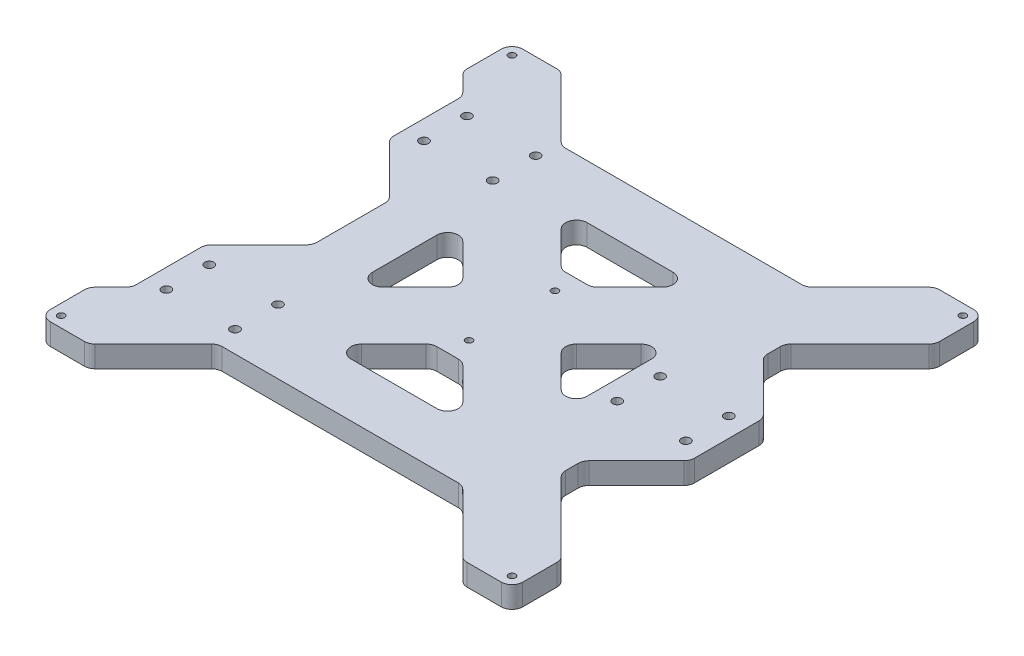
SolidWorks part; units mm, degrees
material "Стекло"
ref_plane "Спереди" through (0, 0, 0) normal (0, 0, 1) x (1, 0, 0)
ref_plane "Сверху" through (0, 0, 0) normal (0, 1, 0) x (1, 0, 0)
ref_plane "Справа" through (0, 0, 0) normal (1, 0, 0) x (0, 0, -1)
sketch "Эскиз1" plane through (0, 0, 0) normal (0, 1, 0) x (1, 0, 0)
  line L0 (-91.6084, 0) -> (86.7133, 0) construction
  line L1 (0, 12.0467) -> (0, -12.5306) construction
  line L2 (-275.537, 125) -> (163.8032, 125) construction
  line L3 (-105, 105) -> (105, 105) construction
  line L4 (-105, 105) -> (-105, -105) construction
  line L5 (-105, -105) -> (105, -105) construction
  line L6 (105, 105) -> (105, -105) construction
  line L7 (-105, 105) -> (105, -105) construction
  line L8 (-105, -105) -> (105, 105) construction
  line L9 (-105, 110) -> (-89.1421, 110)
  line L10 (-55, 125) -> (55, 125) construction
  line L11 (-55, 125) -> (-55, 80) construction
  line L12 (-55, 80) -> (55, 80)
  line L13 (55, 125) -> (55, 80) construction
  line L14 (58.5355, 81.4645) -> (85.6066, 108.5355)
  line L15 (105, 110) -> (89.1421, 110)
  line L16 (-110, 105) -> (-110, 89.1421)
  line L17 (-75, 244.1659) -> (-75, -244.1659) construction
  line L18 (75, 229.144) -> (75, -229.144) construction
  line L19 (-85.6066, 108.5355) -> (-58.5355, 81.4645)
  line L20 (-55, 75) -> (-95, 75) construction
  line L21 (-55, 75) -> (-55, 45) construction
  line L22 (-55, 45) -> (-95, 45) construction
  line L23 (-95, 75) -> (-95, 45) construction
  line L24 (-55, 75) -> (-95, 45) construction
  line L25 (-55, 45) -> (-95, 75) construction
  line L26 (-55, -45) -> (-95, -45) construction
  line L27 (-55, -45) -> (-55, -75) construction
  line L28 (-55, -75) -> (-95, -75) construction
  line L29 (-95, -45) -> (-95, -75) construction
  line L30 (-55, -45) -> (-95, -75) construction
  line L31 (-55, -75) -> (-95, -45) construction
  line L32 (-101.4645, 78.5355) -> (-108.5355, 85.6066)
  line L33 (-100, 45) -> (-100, 75)
  line L34 (-98.5355, 41.4645) -> (-76.4645, 19.3934)
  line L35 (-110, -105) -> (-110, -89.1421)
  line L36 (-76.4645, -19.3934) -> (-98.5355, -41.4645)
  line L37 (-100, -45) -> (-100, -75)
  line L38 (-101.4645, -78.5355) -> (-108.5355, -85.6066)
  line L39 (-75, 15.8579) -> (-75, -15.8579)
  line L40 (110, 105) -> (110, 89.1421)
  line L41 (95, -15) -> (55, -15) construction
  line L42 (95, -15) -> (95, 15) construction
  line L43 (95, 15) -> (55, 15) construction
  line L44 (55, -15) -> (55, 15) construction
  line L45 (95, -15) -> (55, 15) construction
  line L46 (95, 15) -> (55, -15) construction
  line L47 (108.5355, 85.6066) -> (76.4645, 53.5355)
  line L48 (75, 50) -> (75, 44.1421)
  line L49 (98.5355, 18.5355) -> (76.4645, 40.6066)
  line L50 (100, 15) -> (100, -15)
  line L51 (110, -105) -> (110, -89.1421)
  line L52 (108.5355, -85.6066) -> (76.4645, -53.5355)
  line L53 (98.5355, -18.5355) -> (76.4645, -40.6066)
  line L54 (75, -44.1421) -> (75, -50)
  line L55 (-105, -110) -> (-89.1421, -110)
  line L56 (105, -110) -> (89.1421, -110)
  line L57 (-58.5355, -81.4645) -> (-85.6066, -108.5355)
  line L58 (58.5355, -81.4645) -> (85.6066, -108.5355)
  line L59 (-159.2512, -80) -> (161.4197, -80) construction
  line L60 (-55, -80) -> (55, -80)
  line L61 (-23.5355, -46.4645) -> (-8.5355, -31.4645)
  line L62 (-91, 70) -> (-59, 70) construction
  line L63 (-91, 70) -> (-91, 50) construction
  line L64 (-91, 50) -> (-59, 50) construction
  line L65 (-59, 70) -> (-59, 50) construction
  line L66 (-91, 70) -> (-59, 50) construction
  line L67 (-91, 50) -> (-59, 70) construction
  line L68 (-91, -70) -> (-59, -70) construction
  line L69 (-91, -70) -> (-91, -50) construction
  line L70 (-91, -50) -> (-59, -50) construction
  line L71 (-59, -70) -> (-59, -50) construction
  line L72 (-91, -70) -> (-59, -50) construction
  line L73 (-91, -50) -> (-59, -70) construction
  line L74 (59, 10) -> (91, 10) construction
  line L75 (59, 10) -> (59, -10) construction
  line L76 (59, -10) -> (91, -10) construction
  line L77 (91, 10) -> (91, -10) construction
  line L78 (59, 10) -> (91, -10) construction
  line L79 (59, -10) -> (91, 10) construction
  line L80 (-13.5, 25) -> (13.5, 25) construction
  line L81 (-13.5, 25) -> (-13.5, -25) construction
  line L82 (-13.5, -25) -> (13.5, -25) construction
  line L83 (13.5, 25) -> (13.5, -25) construction
  line L84 (-13.5, 25) -> (13.5, -25) construction
  line L85 (-13.5, -25) -> (13.5, 25) construction
  line L86 (23.5355, 46.4645) -> (8.5355, 31.4645)
  line L87 (23.5355, -46.4645) -> (8.5355, -31.4645)
  line L88 (-5, 30) -> (5, 30)
  line L89 (-20, 55) -> (20, 55)
  line L90 (-23.5355, 46.4645) -> (-8.5355, 31.4645)
  line L91 (-20, -55) -> (20, -55)
  line L92 (-5, -30) -> (5, -30)
  line L93 (-50, 15) -> (-50, -15)
  line L94 (-41.4645, 18.5355) -> (-26.4645, 3.5355)
  line L95 (-41.4645, -18.5355) -> (-26.4645, -3.5355)
  line L96 (-18.5, -10) -> (-18.5, 15)
  line L97 (41.4645, 18.5355) -> (26.4645, 3.5355)
  line L98 (41.4645, -18.5355) -> (26.4645, -3.5355)
  line L99 (50, 15) -> (50, -15)
  arc A0 (-105, 110) -> (-110, 105) centre (-105, 105) ccw
  arc A1 (110, 105) -> (105, 110) centre (105, 105) ccw
  circle A2 centre (105, 105) radius 1.6
  arc A3 (-110, -105) -> (-105, -110) centre (-105, -105) ccw
  arc A4 (-58.5355, 81.4645) -> (-55, 80) centre (-55, 85) ccw
  arc A5 (-85.6066, 108.5355) -> (-89.1421, 110) centre (-89.1421, 105) ccw
  arc A6 (55, 80) -> (58.5355, 81.4645) centre (55, 85) ccw
  arc A7 (89.1421, 110) -> (85.6066, 108.5355) centre (89.1421, 105) ccw
  arc A8 (-110, 89.1421) -> (-108.5355, 85.6066) centre (-105, 89.1421) ccw
  arc A9 (-108.5355, -85.6066) -> (-110, -89.1421) centre (-105, -89.1421) ccw
  arc A10 (-100, 75) -> (-101.4645, 78.5355) centre (-105, 75) ccw
  arc A11 (-75, 15.8579) -> (-76.4645, 19.3934) centre (-80, 15.8579) ccw
  arc A12 (-100, 45) -> (-98.5355, 41.4645) centre (-95, 45) ccw
  arc A13 (-98.5355, -41.4645) -> (-100, -45) centre (-95, -45) ccw
  arc A14 (-101.4645, -78.5355) -> (-100, -75) centre (-105, -75) ccw
  arc A15 (-76.4645, -19.3934) -> (-75, -15.8579) centre (-80, -15.8579) ccw
  arc A16 (108.5355, 85.6066) -> (110, 89.1421) centre (105, 89.1421) ccw
  arc A17 (76.4645, 53.5355) -> (75, 50) centre (80, 50) ccw
  arc A18 (100, 15) -> (98.5355, 18.5355) centre (95, 15) ccw
  arc A19 (75, 44.1421) -> (76.4645, 40.6066) centre (80, 44.1421) ccw
  arc A20 (98.5355, -18.5355) -> (100, -15) centre (95, -15) ccw
  arc A21 (76.4645, -40.6066) -> (75, -44.1421) centre (80, -44.1421) ccw
  arc A22 (110, -89.1421) -> (108.5355, -85.6066) centre (105, -89.1421) ccw
  arc A23 (75, -50) -> (76.4645, -53.5355) centre (80, -50) ccw
  arc A24 (-89.1421, -110) -> (-85.6066, -108.5355) centre (-89.1421, -105) ccw
  arc A25 (85.6066, -108.5355) -> (89.1421, -110) centre (89.1421, -105) ccw
  arc A26 (58.5355, -81.4645) -> (55, -80) centre (55, -85) ccw
  arc A27 (-55, -80) -> (-58.5355, -81.4645) centre (-55, -85) ccw
  arc A28 (105, -110) -> (110, -105) centre (105, -105) ccw
  circle A29 centre (105, -105) radius 1.6
  circle A30 centre (-105, -105) radius 1.6
  circle A31 centre (-105, 105) radius 1.6
  circle A32 centre (-91, 70) radius 2.1
  circle A33 centre (-59, 70) radius 2.1
  circle A34 centre (-59, 50) radius 2.1
  circle A35 centre (-91, 50) radius 2.1
  circle A36 centre (-59, -50) radius 2.1
  circle A37 centre (-91, -50) radius 2.1
  circle A38 centre (-91, -70) radius 2.1
  circle A39 centre (-59, -70) radius 2.1
  circle A40 centre (91, -10) radius 2.1
  circle A41 centre (59, -10) radius 2.1
  circle A42 centre (59, 10) radius 2.1
  circle A43 centre (91, 10) radius 2.1
  circle A44 centre (0, -20) radius 1.6
  circle A45 centre (0, 20) radius 1.6
  arc A46 (-20, 55) -> (-23.5355, 46.4645) centre (-20, 50) ccw
  arc A47 (23.5355, 46.4645) -> (20, 55) centre (20, 50) ccw
  arc A48 (-8.5355, 31.4645) -> (-5, 30) centre (-5, 35) ccw
  arc A49 (5, 30) -> (8.5355, 31.4645) centre (5, 35) ccw
  arc A50 (-23.5355, -46.4645) -> (-20, -55) centre (-20, -50) ccw
  arc A51 (20, -55) -> (23.5355, -46.4645) centre (20, -50) ccw
  arc A52 (-5, -30) -> (-8.5355, -31.4645) centre (-5, -35) ccw
  arc A53 (8.5355, -31.4645) -> (5, -30) centre (5, -35) ccw
  arc A54 (-41.4645, 18.5355) -> (-50, 15) centre (-45, 15) ccw
  arc A55 (-50, -15) -> (-41.4645, -18.5355) centre (-45, -15) ccw
  arc A56 (-26.4645, -3.5355) -> (-26.4645, 3.5355) centre (-30, 0) ccw
  arc A57 (26.4645, 3.5355) -> (26.4645, -3.5355) centre (30, 0) ccw
  arc A58 (50, 15) -> (41.4645, 18.5355) centre (45, 15) ccw
  arc A59 (41.4645, -18.5355) -> (50, -15) centre (45, -15) ccw
  point P4 (0, 0)
  point P20 (0, 125)
  point P37 (-75, 0)
  point P38 (75, 0)
  point P39 (-75, 60)
  point P44 (-75, -60)
  point P61 (75, 0)
  point P115 (-75, 60)
  point P123 (-75, -60)
  point P128 (75, 0)
  point P145 (0, 0)
  dimension "D3" = 10
  dimension "D7" = 5
  dimension "D15" = 3.2
  dimension "D18" = 4.2
  dimension "D1" = 210
  dimension "D2" = 210
  dimension "D4" = 125
  dimension "D5" = 45
  dimension "D6" = 110
  dimension "D8" = 75
  dimension "D9" = 75
  dimension "D10" = 30
  dimension "D11" = 40
  dimension "D12" = 60
  dimension "D13" = 60
  dimension "D14" = 30
  dimension "D16" = 32
  dimension "D17" = 20
  dimension "D19" = 50
  dimension "D20" = 27
  dimension "D21" = 20
  dimension "D22" = 20
  dimension "D24" = 5
  dimension "D23" = 25
  dimension "D25" = 5
  dimension "D26" = 25
  dimension "D27" = 25
  dimension "D28" = 5
  dimension "D29" = 5
extrude "Бобышка-Вытянуть1" add sketch "Эскиз1" along normal blind 10
equation "\"D4@Эскиз1\"=450/2-200/2"
equation "\"D8@Эскиз1\"=150/2"
equation "\"D9@Эскиз1\"=150/2"
